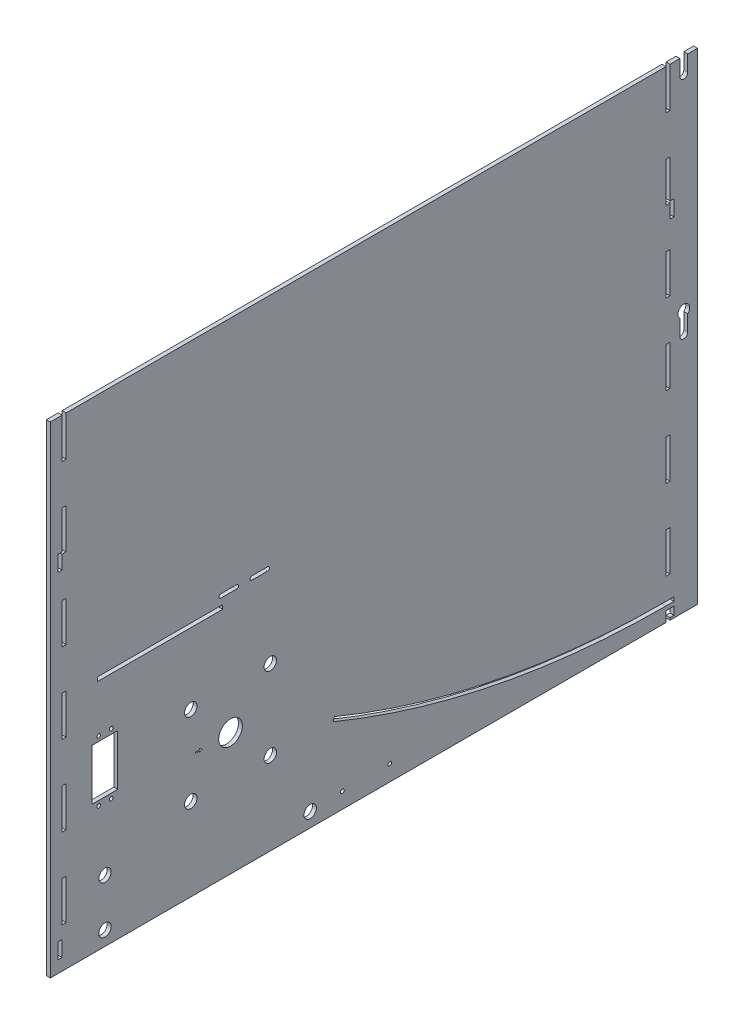
SolidWorks part; units mm, degrees
ref_plane "Front Plane" through (0, 0, 0) normal (0, 0, 1) x (1, 0, 0)
ref_plane "Top Plane" through (0, 0, 0) normal (0, 1, 0) x (1, 0, 0)
ref_plane "Right Plane" through (0, 0, 0) normal (1, 0, 0) x (0, 0, -1)
sketch "Sketch1" plane through (0, 0, 0) normal (1, 0, 0) x (0, 0, -1)
  line L0 (-141.0275, 130.552) -> (-77.0275, 130.552) construction
  line L1 (-244.475, 387.35) -> (244.475, 387.35)
  line L2 (-244.475, 387.35) -> (-244.475, 0)
  line L3 (-244.475, 0) -> (244.475, 0)
  line L4 (244.475, 387.35) -> (244.475, 0)
  line L5 (-77.0275, 130.552) -> (-77.0275, 66.552) construction
  line L6 (-77.0275, 66.552) -> (-141.0275, 66.552) construction
  line L7 (-141.0275, 66.552) -> (-141.0275, 130.552) construction
  line L8 (-215.1157, 149.1948) -> (-204.9557, 149.1948) construction
  line L9 (-220.2857, 145.2948) -> (-199.7857, 145.2948)
  line L10 (-220.2857, 145.2948) -> (-220.2857, 104.2948)
  line L11 (-220.2857, 104.2948) -> (-199.7857, 104.2948)
  line L12 (-199.7857, 145.2948) -> (-199.7857, 104.2948)
  line L15 (-204.9557, 100.3948) -> (-215.1157, 100.3948) construction
  line L18 (-210.0357, 100.3948) -> (-210.0357, 149.1948) construction
  line L19 (-220.2857, 124.7948) -> (-199.7857, 124.7948) construction
  line L20 (-241.3, 387.35) -> (-241.3, 0) construction
  line L21 (241.3, 387.35) -> (241.3, 0) construction
  line L22 (-244.475, 193.675) -> (-241.3, 193.675) construction
  line L23 (244.475, 193.675) -> (241.3, 193.675) construction
  line L24 (-244.475, 6.35) -> (244.475, 6.35) construction
  line L25 (-241.3, 190.754) -> (-215.9, 190.754) construction
  line L26 (-115.3775, 190.754) -> (-109.0275, 190.754) construction
  line L27 (-215.9, 190.754) -> (-115.3775, 190.754)
  line L28 (-215.9, 190.754) -> (-215.9, 187.579)
  line L29 (-215.9, 187.579) -> (-115.3775, 187.579)
  line L30 (-115.3775, 190.754) -> (-115.3775, 187.579)
  line L31 (-109.0275, 190.754) -> (-109.0275, 187.579) construction
  line L32 (-109.0275, 187.579) -> (-115.3775, 187.579) construction
  line L33 (-215.9, 187.579) -> (-241.3, 187.579) construction
  line L34 (-26.6311, 64.8518) -> (-25.4161, 67.7851)
  line L35 (241.3, 11.557) -> (241.3, 14.732)
  line L36 (-26.0236, 66.3185) -> (-68.1062, 83.7497) construction
  line L37 (241.3, 13.1445) -> (249.9158, 13.1445) construction
  line L38 (-26.0236, 66.3185) -> (-57.3534, 66.3185) construction
  line L39 (-91.8775, 197.579) -> (-116.8775, 197.579) construction
  line L40 (-244.475, 387.35) -> (-254, 387.35)
  line L41 (-244.475, 387.35) -> (-244.475, 0)
  line L42 (-244.475, 0) -> (-254, 0)
  line L43 (-254, 387.35) -> (-254, 0)
  line L44 (244.475, 387.35) -> (266.7, 387.35)
  line L45 (244.475, 387.35) -> (244.475, 0)
  line L46 (244.475, 0) -> (266.7, 0)
  line L47 (266.7, 387.35) -> (266.7, 0)
  line L48 (-116.8775, 199.079) -> (-104.1775, 199.079)
  line L49 (-104.1775, 196.079) -> (-116.8775, 196.079)
  line L50 (-91.8775, 196.079) -> (-79.1775, 196.079)
  line L51 (-79.1775, 199.079) -> (-91.8775, 199.079)
  circle A0 centre (-109.0275, 98.552) radius 89.027 construction
  circle A1 centre (-109.0275, 98.552) radius 9.525
  circle A2 centre (-141.0275, 130.552) radius 5
  circle A3 centre (-77.0275, 130.552) radius 5
  circle A4 centre (-141.0275, 66.552) radius 5
  circle A5 centre (-77.0275, 66.552) radius 5
  circle A10 centre (-215.1157, 149.1948) radius 1.5
  circle A11 centre (-204.9557, 149.1948) radius 1.5
  circle A12 centre (-215.1157, 100.3948) radius 1.5
  circle A13 centre (-204.9557, 100.3948) radius 1.5
  arc A14 (241.3, 11.557) -> (-26.6311, 64.8518) centre (241.3, 711.6946) cw
  arc A15 (241.3, 14.732) -> (-25.4161, 67.7851) centre (241.3, 711.6946) cw
  arc A16 (241.3, 13.1445) -> (-26.0236, 66.3185) centre (241.3, 711.6946) cw construction
  circle A17 centre (-116.8775, 197.579) radius 1.5
  circle A18 centre (-91.8775, 197.579) radius 1.5
  arc A19 (-104.1775, 199.079) -> (-104.1775, 196.079) centre (-104.1775, 197.579) cw
  arc A20 (-79.1775, 196.079) -> (-79.1775, 199.079) centre (-79.1775, 197.579) ccw
  point P16 (-109.0275, 130.552)
  point P18 (-141.0275, 98.552)
  point P31 (-210.0357, 104.2948)
  point P34 (-210.0357, 124.7948)
  point P38 (-198.0545, 98.552)
  point P57 (0, 0)
  point P60 (-109.0275, 9.525)
  dimension "D3" = 178.054
  dimension "D5" = 10
  dimension "D6" = 19.05
  dimension "D8" = 3
  dimension "D28" = 3
  dimension "D4" = 64
  dimension "D7" = 10.16
  dimension "D9" = 20.5
  dimension "D10" = 41
  dimension "D11" = 48.8
  dimension "D12" = 11.9812
  dimension "D13" = 26.2428
  dimension "D14" = 3.175
  dimension "D15" = 482.6
  dimension "D16" = 6.35
  dimension "D2" = 381
  dimension "D17" = 25.4
  dimension "D18" = 3.175
  dimension "D19" = 6.35
  dimension "D20" = 100.5225
  dimension "D21" = 9.525
  dimension "D23" = 3.175
  dimension "D24" = 13.1445
  dimension "D25" = 22.5
  dimension "D26" = 9.525
  dimension "D27" = 22.225
  dimension "D29" = 6.825
  dimension "D30" = 25
  dimension "D31" = 12.7
  dimension "D32" = 1.5
  dimension "D22" = 274.32
extrude "Boss-Extrude1" add sketch "Sketch1" along normal blind 3.175 contours L4 L1 L2 L3 A15 L35 A14 L34 A13 A12 A11 A10 A5 A4 A3 A2 A1 L9 L12 L11 L10 L27 L30 L29 L28 | L47 L44 L4 L46 | L40 L43 L42 L2
sketch "Sketch2" plane through (0, 0, 0) normal (-1, 0, 0) x (0, 0, 1)
  line L34 (-241.3, 387.35) -> (-241.3, 0) construction
  line L35 (-244.475, 387.35) -> (-241.3, 387.35)
  line L36 (-244.475, 387.35) -> (-244.475, 355.0708)
  line L37 (-244.475, 355.0708) -> (-241.3, 355.0708)
  line L38 (-241.3, 387.35) -> (-241.3, 355.0708)
  line L39 (241.3, 387.35) -> (241.3, 0) construction
  line L40 (244.475, 387.35) -> (241.3, 387.35)
  line L41 (244.475, 387.35) -> (244.475, 355.0708)
  line L42 (244.475, 355.0708) -> (241.3, 355.0708)
  line L43 (241.3, 387.35) -> (241.3, 355.0708)
  line L44 (-244.475, 355.0708) -> (-244.475, 322.7917)
  line L45 (-244.475, 355.0708) -> (-241.3, 355.0708)
  line L46 (-241.3, 355.0708) -> (-241.3, 322.7917)
  line L47 (-244.475, 322.7917) -> (-241.3, 322.7917)
  line L48 (244.475, 355.0708) -> (244.475, 322.7917)
  line L49 (244.475, 355.0708) -> (241.3, 355.0708)
  line L50 (241.3, 355.0708) -> (241.3, 322.7917)
  line L51 (244.475, 322.7917) -> (241.3, 322.7917)
  line L52 (-244.475, 322.7917) -> (-244.475, 290.5125)
  line L53 (-244.475, 322.7917) -> (-241.3, 322.7917)
  line L54 (-241.3, 322.7917) -> (-241.3, 290.5125)
  line L55 (-244.475, 290.5125) -> (-241.3, 290.5125)
  line L56 (244.475, 322.7917) -> (244.475, 290.5125)
  line L57 (244.475, 322.7917) -> (241.3, 322.7917)
  line L58 (241.3, 322.7917) -> (241.3, 290.5125)
  line L59 (244.475, 290.5125) -> (241.3, 290.5125)
  line L60 (-244.475, 290.5125) -> (-244.475, 258.2333)
  line L61 (-244.475, 290.5125) -> (-241.3, 290.5125)
  line L62 (-241.3, 290.5125) -> (-241.3, 258.2333)
  line L63 (-244.475, 258.2333) -> (-241.3, 258.2333)
  line L64 (244.475, 290.5125) -> (244.475, 258.2333)
  line L65 (244.475, 290.5125) -> (241.3, 290.5125)
  line L66 (241.3, 290.5125) -> (241.3, 258.2333)
  line L67 (244.475, 258.2333) -> (241.3, 258.2333)
  line L68 (-244.475, 258.2333) -> (-244.475, 225.9542)
  line L69 (-244.475, 258.2333) -> (-241.3, 258.2333)
  line L70 (-241.3, 258.2333) -> (-241.3, 225.9542)
  line L71 (-244.475, 225.9542) -> (-241.3, 225.9542)
  line L72 (244.475, 258.2333) -> (244.475, 225.9542)
  line L73 (244.475, 258.2333) -> (241.3, 258.2333)
  line L74 (241.3, 258.2333) -> (241.3, 225.9542)
  line L75 (244.475, 225.9542) -> (241.3, 225.9542)
  line L76 (-244.475, 225.9542) -> (-244.475, 193.675)
  line L77 (-244.475, 225.9542) -> (-241.3, 225.9542)
  line L78 (-241.3, 225.9542) -> (-241.3, 193.675)
  line L79 (-244.475, 193.675) -> (-241.3, 193.675)
  line L80 (244.475, 225.9542) -> (244.475, 193.675)
  line L81 (244.475, 225.9542) -> (241.3, 225.9542)
  line L82 (241.3, 225.9542) -> (241.3, 193.675)
  line L83 (244.475, 193.675) -> (241.3, 193.675)
  line L84 (-244.475, 193.675) -> (-244.475, 161.3958)
  line L85 (-244.475, 193.675) -> (-241.3, 193.675)
  line L86 (-241.3, 193.675) -> (-241.3, 161.3958)
  line L87 (-244.475, 161.3958) -> (-241.3, 161.3958)
  line L88 (244.475, 193.675) -> (244.475, 161.3958)
  line L89 (244.475, 193.675) -> (241.3, 193.675)
  line L90 (241.3, 193.675) -> (241.3, 161.3958)
  line L91 (244.475, 161.3958) -> (241.3, 161.3958)
  line L92 (-244.475, 161.3958) -> (-244.475, 129.1167)
  line L93 (-244.475, 161.3958) -> (-241.3, 161.3958)
  line L94 (-241.3, 161.3958) -> (-241.3, 129.1167)
  line L95 (-244.475, 129.1167) -> (-241.3, 129.1167)
  line L96 (244.475, 161.3958) -> (244.475, 129.1167)
  line L97 (244.475, 161.3958) -> (241.3, 161.3958)
  line L98 (241.3, 161.3958) -> (241.3, 129.1167)
  line L99 (244.475, 129.1167) -> (241.3, 129.1167)
  line L100 (-244.475, 129.1167) -> (-244.475, 96.8375)
  line L101 (-244.475, 129.1167) -> (-241.3, 129.1167)
  line L102 (-241.3, 129.1167) -> (-241.3, 96.8375)
  line L103 (-244.475, 96.8375) -> (-241.3, 96.8375)
  line L104 (244.475, 129.1167) -> (244.475, 96.8375)
  line L105 (244.475, 129.1167) -> (241.3, 129.1167)
  line L106 (241.3, 129.1167) -> (241.3, 96.8375)
  line L107 (244.475, 96.8375) -> (241.3, 96.8375)
  line L108 (0, 387.35) -> (0, 0) construction
  line L109 (244.475, 387.35) -> (-244.475, 387.35) construction
  line L110 (-244.475, 96.8375) -> (-244.475, 64.5583)
  line L111 (-244.475, 96.8375) -> (-241.3, 96.8375)
  line L112 (-241.3, 96.8375) -> (-241.3, 64.5583)
  line L113 (-244.475, 64.5583) -> (-241.3, 64.5583)
  line L114 (244.475, 96.8375) -> (244.475, 64.5583)
  line L115 (244.475, 96.8375) -> (241.3, 96.8375)
  line L116 (241.3, 96.8375) -> (241.3, 64.5583)
  line L117 (244.475, 64.5583) -> (241.3, 64.5583)
  line L118 (-244.475, 64.5583) -> (-244.475, 32.2792)
  line L119 (-244.475, 64.5583) -> (-241.3, 64.5583)
  line L120 (-241.3, 64.5583) -> (-241.3, 32.2792)
  line L121 (-244.475, 32.2792) -> (-241.3, 32.2792)
  line L122 (244.475, 64.5583) -> (244.475, 32.2792)
  line L123 (244.475, 64.5583) -> (241.3, 64.5583)
  line L124 (241.3, 64.5583) -> (241.3, 32.2792)
  line L125 (244.475, 32.2792) -> (241.3, 32.2792)
  line L126 (-244.475, 32.2792) -> (-244.475, 0)
  line L127 (-244.475, 32.2792) -> (-241.3, 32.2792)
  line L128 (-241.3, 32.2792) -> (-241.3, 0)
  line L129 (-244.475, 0) -> (-241.3, 0)
  line L130 (244.475, 32.2792) -> (244.475, 0)
  line L131 (244.475, 32.2792) -> (241.3, 32.2792)
  line L132 (241.3, 32.2792) -> (241.3, 0)
  line L133 (244.475, 0) -> (241.3, 0)
  line M136 (254, 387.35) -> (-266.7, 387.35)
  dimension "D2" = 387.35
  dimension "D3" = 32.2792
  dimension "D1" = 12
extrude "Cut-Extrude1" cut sketch "Sketch2" against normal through all contours L118 L121 L120 L113 | L100 L103 L102 L95 | L84 L87 L86 L79 | L52 L55 L54 L47 | L38 L36 L37 M136 | L68 L71 L70 L63 | L43 L42 L41 M136 | L59 L56 L51 L58 | L75 L72 L67 L74 | L91 L88 L83 L90 | L107 L104 L99 L106 | L125 L122 L117 L124
sketch "Sketch3" plane through (0, 0, 0) normal (-1, 0, 0) x (0, 0, 1)
  line L0 (-258.7625, 206.375) -> (-258.7625, 193.675)
  line L1 (-252.4125, 193.675) -> (-252.4125, 206.375)
  line L2 (-258.7625, 387.35) -> (-258.7625, 374.65)
  line L3 (-244.475, 387.35) -> (-266.7, 387.35) construction
  line L4 (-252.4125, 374.65) -> (-252.4125, 387.35)
  line L5 (-258.7625, 387.35) -> (-252.4125, 387.35)
  line L6 (-255.5875, 374.65) -> (-255.5875, 193.675) construction
  line L7 (-266.7, 387.35) -> (-266.7, 0) construction
  line L9 (-241.3, 11.557) -> (-247.65, 11.557)
  line L10 (-241.3, 11.557) -> (-241.3, 14.732)
  line L11 (-241.3, 14.732) -> (-247.65, 14.732)
  line L12 (-247.65, 11.557) -> (-247.65, 14.732)
  circle A0 centre (-255.5875, 209.9248) radius 4.7625
  arc A1 (-258.7625, 193.675) -> (-252.4125, 193.675) centre (-255.5875, 193.675) ccw
  arc A2 (-258.7625, 374.65) -> (-252.4125, 374.65) centre (-255.5875, 374.65) ccw
  point P16 (-255.5875, 387.35)
  point P17 (-255.5875, 387.35)
  point P24 (-266.7, 193.675)
  dimension "D1" = 3.175
  dimension "D2" = 9.525
  dimension "D3" = 12.7
  dimension "D4" = 6.35
extrude "Cut-Extrude2" cut sketch "Sketch3" against normal through all
sketch "Sketch4" plane through (0, 0, 0) normal (-1, 0, 0) x (0, 0, 1)
  line L0 (210.0357, 49.5948) -> (210.0357, 11.4948) construction
  line L1 (210.0357, 11.4948) -> (44.9357, 11.4948) construction
  line L2 (210.0357, 49.5948) -> (210.0357, 100.3948) construction
  circle A0 centre (210.0357, 49.5948) radius 5
  circle A1 centre (44.9357, 11.4948) radius 5
  circle A2 centre (210.0357, 11.4948) radius 5
  dimension "D1" = 10
  dimension "D2" = 50.8
  dimension "D3" = 38.1
  dimension "D4" = 165.1
extrude "Cut-Extrude3" cut sketch "Sketch4" against normal through all
sketch "Sketch5" plane through (0, 0, 0) normal (-1, 0, 0) x (0, 0, 1)
  line L0 (244.475, 0) -> (-244.475, 0) construction
  line L1 (-19.05, 12.7) -> (19.05, 12.7) construction
  circle A0 centre (-19.05, 12.7) radius 1.5
  circle A1 centre (19.05, 12.7) radius 1.5
  point P6 (0, 12.7)
  dimension "D3" = 3
  dimension "D1" = 38.1
  dimension "D2" = 12.7
extrude "Cut-Extrude4" cut sketch "Sketch5" against normal through all
sketch "Sketch6" plane through (0, 0, 0) normal (-1, 0, 0) x (0, 0, 1)
  line L0 (244.475, 387.35) -> (244.475, 355.0708) construction
  line L1 (244.475, 292.1) -> (247.65, 292.1)
  line L2 (244.475, 292.1) -> (244.475, 279.4)
  line L3 (244.475, 279.4) -> (247.65, 279.4)
  line L4 (247.65, 292.1) -> (247.65, 279.4)
  line L6 (244.475, 64.5583) -> (244.475, 32.2792) construction
  line L7 (244.475, 9.525) -> (247.65, 9.525)
  line L8 (244.475, 9.525) -> (244.475, 22.225)
  line L9 (244.475, 22.225) -> (247.65, 22.225)
  line L10 (247.65, 9.525) -> (247.65, 22.225)
  line L11 (-244.475, 322.7917) -> (-244.475, 290.5125) construction
  line L12 (-247.65, 279.4) -> (-244.475, 279.4)
  line L13 (-247.65, 279.4) -> (-247.65, 292.1)
  line L14 (-247.65, 292.1) -> (-244.475, 292.1)
  line L15 (-244.475, 279.4) -> (-244.475, 292.1)
  line L16 (-244.475, 64.5583) -> (-244.475, 32.2792) construction
  line L17 (-244.475, 1.905) -> (-247.65, 1.905)
  line L18 (-244.475, 1.905) -> (-244.475, 8.255)
  line L19 (-244.475, 8.255) -> (-247.65, 8.255)
  line L20 (-247.65, 1.905) -> (-247.65, 8.255)
  line L21 (254, 387.35) -> (244.475, 387.35) construction
  line L24 (254, 0) -> (-266.7, 0) construction
  line L26 (-244.475, 8.255) -> (-241.3, 8.255)
  line L27 (-244.475, 8.255) -> (-244.475, 0)
  line L28 (-244.475, 0) -> (-241.3, 0)
  line L29 (-241.3, 8.255) -> (-241.3, 0)
  circle A0 centre (-247.65, 5.08) radius 1.5 construction
  point P24 (247.65, 14.605)
  point P27 (244.475, 8.578)
  point P28 (244.475, 285.75)
  dimension "D4" = 3
  dimension "D2" = 3.175
  dimension "D3" = 12.7
  dimension "D5" = 6.35
  dimension "D6" = 3.175
  dimension "D7" = 8.255
  dimension "D8" = 9.525
  dimension "D1" = 101.6
extrude "Cut-Extrude5" cut sketch "Sketch6" against normal through all contours L29 L26 L18 L27 L28 | L20 L17 L18 L19 | L12 L15 L14 L13 | L4 L1 L2 L3 | L7 L10 L9 L8
sketch "Sketch7" plane through (0, 0, 0) normal (-1, 0, 0) x (0, 0, 1)
  line L0 (118.5525, 98.552) -> (137.1247, 98.552) construction
  line L1 (137.1247, 98.9489) -> (137.1247, 98.1551)
  line L2 (137.1247, 98.1551) -> (133.9497, 98.1551)
  line L7 (133.9497, 98.9489) -> (137.1247, 98.9489)
  line L17 (131.8875, 98.5393) -> (131.8875, 98.5647) construction
  line L20 (133.9497, 98.9489) -> (133.9497, 99.7426)
  line L21 (133.9497, 99.7426) -> (131.8875, 98.552)
  line L22 (131.8875, 98.552) -> (133.9497, 97.3614)
  line L23 (133.9497, 97.3614) -> (133.9497, 98.1551)
  circle A0 centre (109.0275, 98.552) radius 9.525 construction
  point P7 (132.1522, 97.2873)
  point P14 (137.1247, 98.552)
  point P15 (131.0348, 99.8517)
  point P16 (0, 0)
  point P17 (0, 0)
  point P18 (131.8875, 98.552)
  dimension "D1" = 0.7937
  dimension "D2" = 30
  dimension "D3" = 13.335
  dimension "D4" = 3.175
  dimension "D5" = 0.0254
  dimension "D6" = 0.7937
extrude "Cut-Extrude6" cut sketch "Sketch7" against normal through all
equation "\"wallThickness\"= .125in"
equation "\"bottomThickness\"= .25"
equation "\"D14@Sketch1\"=\"wallThickness\""
equation "\"D16@Sketch1\"=\"bottomThickness\""
equation "\"D18@Sketch1\"=\"wallThickness\""
equation "\"D23@Sketch1\"=\"wallThickness\""
equation "\"D1@Boss-Extrude1\"=\"wallThickness\""
equation "\"D3@Sketch2\"=\"D2@Sketch2\" / \"D1@Sketch2\""
equation "\"chamberHeight\"= 15"
equation "\"D2@Sketch1\"=\"chamberHeight\""
equation "\"D6@Sketch6\"=\"wallThickness\""
